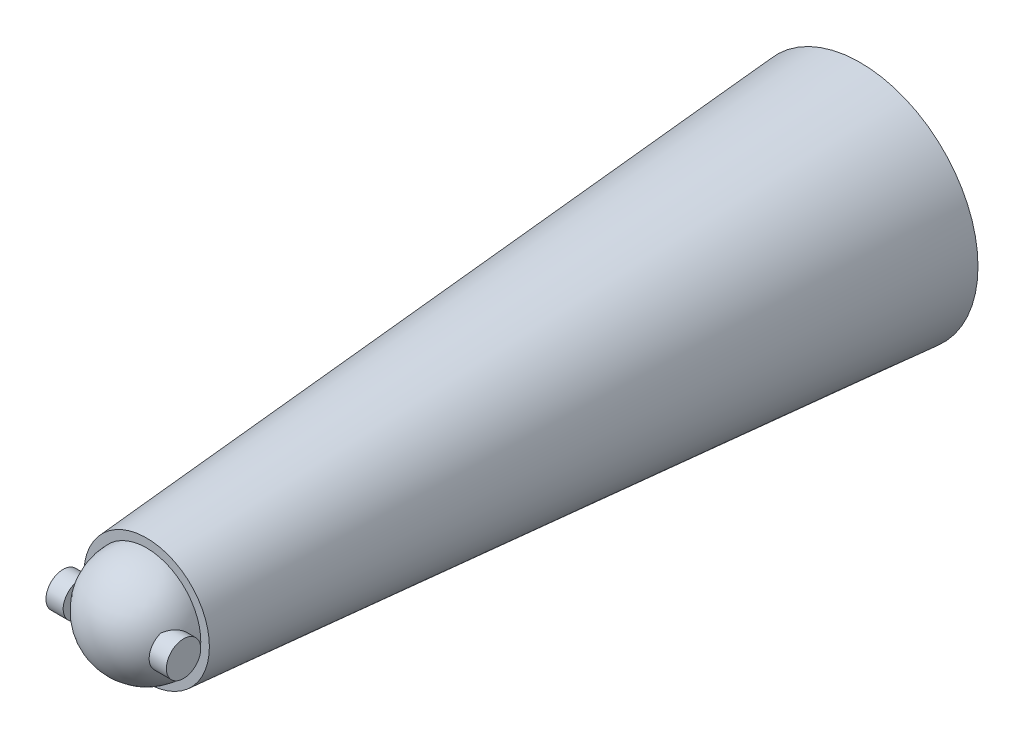
SolidWorks part; units mm, degrees
ref_plane "Front Plane" through (0, 0, 0) normal (0, 0, 1) x (1, 0, 0)
ref_plane "Top Plane" through (0, 0, 0) normal (0, 1, 0) x (1, 0, 0)
ref_plane "Right Plane" through (0, 0, 0) normal (1, 0, 0) x (0, 0, -1)
sketch "Sketch1" plane through (0, 0, 0) normal (0, 0, 1) x (1, 0, 0)
  circle A0 centre (0, 0) radius 68.435
  dimension "D1" = 136.87
extrude "Boss-Extrude1" add sketch "Sketch1" along normal blind 415 draft 4.4
sketch "Sketch2" plane through (0, 0, 415) normal (0, 0, 1) x (1, 0, 0)
  line L0 (0, 31.5025) -> (0, -31.5025)
  arc A0 (0, 31.5025) -> (0, -31.5025) centre (0, 0) ccw
  dimension "D1" = 31.5025
revolve "Revolve1" add sketch "Sketch2" angle 360 about L0
sketch "Sketch3" plane through (0, 0, 0) normal (0, 0, -1) x (-1, 0, 0)
  line L0 (0, 63.435) -> (0, -63.435)
  arc A0 (0, 63.435) -> (0, -63.435) centre (0, 0) ccw
  dimension "D1" = 126.87
revolve "Cut-Revolve1" cut sketch "Sketch3" angle 360 about L0
ref_plane "Plane1" through (55, 0, 0) normal (1, 0, 0) x (0, 0, -1)
sketch "Sketch4" plane through (55, 0, 0) normal (1, 0, 0) x (0, 0, -1)
  circle A0 centre (-16.4433, 0) radius 10
  dimension "D1" = 20
ref_plane "Plane2" through (-55, 0, 0) normal (1, 0, 0) x (0, 0, -1)
sketch "Sketch5" plane through (-55, 0, 0) normal (1, 0, 0) x (0, 0, -1)
  circle A0 centre (-16.4433, 0) radius 10 construction
  circle A1 centre (-16.4433, 0) radius 10
extrude "Cut-Extrude1" cut sketch "Sketch5" against normal blind 10
extrude "Cut-Extrude4" cut sketch "Sketch4" along normal blind 10 contours A0
ref_plane "Plane3" through (25, 0, 0) normal (1, 0, 0) x (0, 0, -1)
ref_plane "Plane4" through (-25, 0, 0) normal (1, 0, 0) x (0, 0, -1)
sketch "Sketch8" plane through (-25, 0, 0) normal (1, 0, 0) x (0, 0, -1)
  circle A0 centre (-428.5215, 0) radius 10
  dimension "D1" = 20
sketch "Sketch9" plane through (25, 0, 0) normal (1, 0, 0) x (0, 0, -1)
  circle A0 centre (-428.5215, 0) radius 10 construction
  circle A1 centre (-428.5215, 0) radius 10
extrude "Boss-Extrude2" add sketch "Sketch9" along normal blind 10
extrude "Boss-Extrude3" add sketch "Sketch8" against normal blind 10 contours A0
